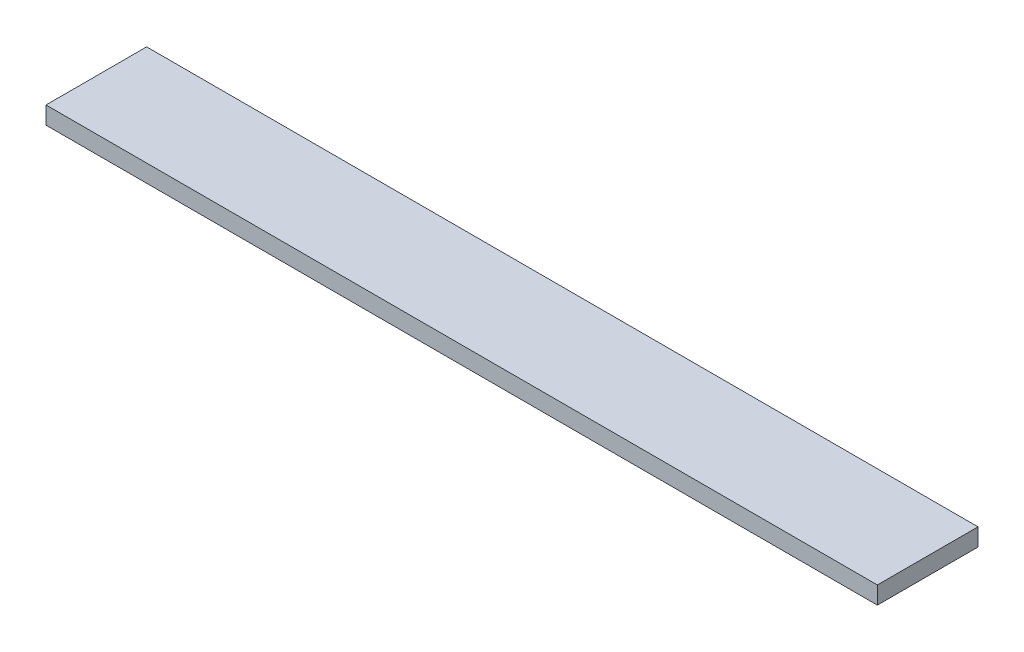
SolidWorks part; units mm, degrees
ref_plane "Front" through (0, 0, 0) normal (0, 0, 1) x (1, 0, 0)
ref_plane "Top" through (0, 0, 0) normal (0, 1, 0) x (1, 0, 0)
ref_plane "Right" through (0, 0, 0) normal (1, 0, 0) x (0, 0, -1)
sketch "Sketch1" plane through (0, 0, 0) normal (0, 1, 0) x (1, 0, 0)
  line L1 (-2413, 584.2) -> (2413, 584.2)
  line L2 (-2413, 584.2) -> (-2413, -584.2)
  line L3 (-2413, -584.2) -> (2413, -584.2)
  line L4 (2413, 584.2) -> (2413, -584.2)
  line L5 (-2413, 584.2) -> (2413, -584.2) construction
  line L6 (-2413, -584.2) -> (2413, 584.2) construction
  point P0 (0, 0)
  dimension "D1" = 4826
  dimension "D2" = 1168.4
extrude "Boss-Extrude1" add sketch "Sketch1" along normal blind 101.6
sketch "Sketch2" plane through (0, 101.6, 0) normal (0, 1, 0) x (1, 0, 0)
  line L0 (2413, -584.2) -> (2413, 584.2) construction
  line L1 (-2413, 584.2) -> (2413, 584.2)
  line L2 (-2413, 584.2) -> (-2413, 0)
  line L3 (-2413, 0) -> (2413, 0)
  line L4 (2413, 584.2) -> (2413, 0)
  line L5 (-2413, -584.2) -> (2413, -584.2) construction
  dimension "D1" = 584.2
extrude "Cut-Extrude1" cut sketch "Sketch2" against normal through all
sketch "Sketch4" [suppressed] plane through (0, 101.6, 0) normal (0, 1, 0) x (1, 0, 0)
  line L0 (2413, 584.2) -> (-2413, 584.2) construction
  line L1 (-2413, -584.2) -> (-2717.8, -584.2)
  line L2 (-2413, -584.2) -> (-2413, 584.2)
  line L3 (-2413, 584.2) -> (-2717.8, 584.2)
  line L4 (-2717.8, -584.2) -> (-2717.8, 584.2)
  line L5 (2413, -584.2) -> (2413, 584.2) construction
  dimension "D1" = 5130.8
extrude "Boss-Extrude2" [suppressed] add sketch "Sketch4" against normal up to surface (101.6 mm away)
